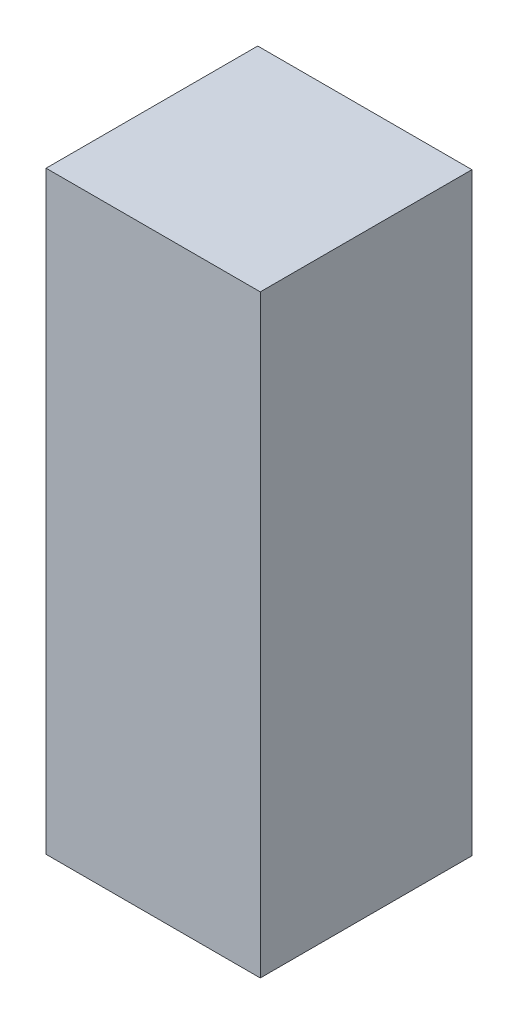
SolidWorks part; units mm, degrees
ref_plane "Front Plane" through (0, 0, 0) normal (0, 0, 1) x (1, 0, 0)
ref_plane "Top Plane" through (0, 0, 0) normal (0, 1, 0) x (1, 0, 0)
ref_plane "Right Plane" through (0, 0, 0) normal (1, 0, 0) x (0, 0, -1)
sketch "Sketch1" plane through (0, 0, 0) normal (1, 0, 0) x (0, 0, -1)
  line L1 (-15.2026, 28.1852) -> (-5.1641, 28.1852)
  line L2 (-15.2026, 28.1852) -> (-15.2026, 0)
  line L3 (-15.2026, 0) -> (-5.1641, 0)
  line L4 (-5.1641, 28.1852) -> (-5.1641, 0)
extrude "Boss-Extrude1" add sketch "Sketch1" along normal blind 10.16
